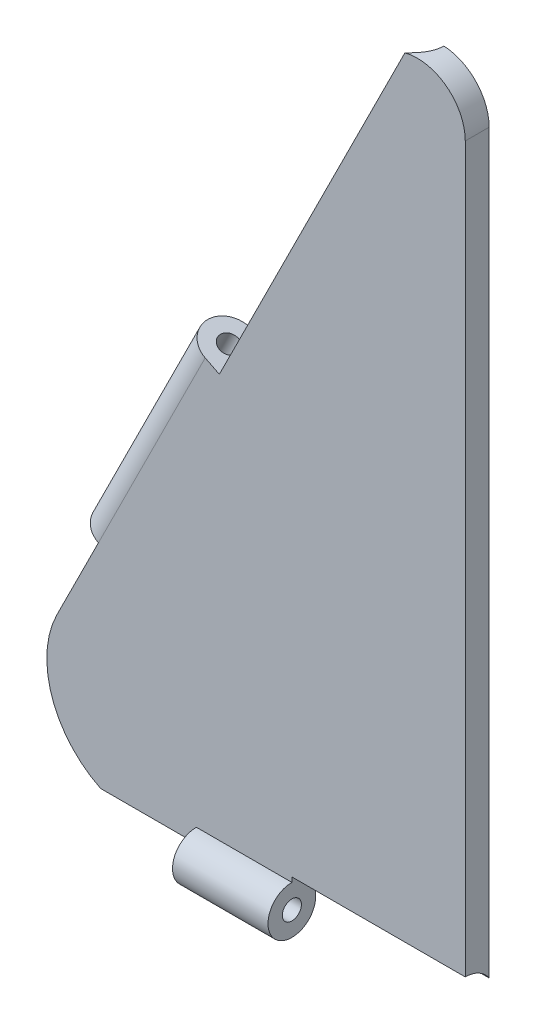
SolidWorks part; units mm, degrees
ref_plane "前视基准面" through (0, 0, 0) normal (0, 0, 1) x (1, 0, 0)
ref_plane "上视基准面" through (0, 0, 0) normal (0, 1, 0) x (1, 0, 0)
ref_plane "右视基准面" through (0, 0, 0) normal (1, 0, 0) x (0, 0, -1)
sketch "草图1" plane through (0, 0, 5) normal (0, 0, 1) x (1, 0, 0)
  line L0 (-531.2593, 335.4243) -> (-597.8429, 202.2571)
  line L1 (-579.9544, 173.3129) -> (-512.3151, 173.3129)
  line L2 (-512.3151, 173.3129) -> (-512.3151, 330.9522)
  arc A0 (-579.9544, 173.3129) -> (-597.8429, 202.2571) centre (-579.9544, 193.3129) cw
  arc A1 (-512.3151, 330.9522) -> (-531.2593, 335.4243) centre (-522.3151, 330.9522) ccw
  point P5 (-612.3151, 173.3129)
  point P8 (-512.3151, 373.3129)
  dimension "D3" = 20
  dimension "D4" = 10
  dimension "D1" = 200
  dimension "D2" = 100
extrude "凸台-拉伸1" add sketch "草图1" along normal blind 5
sketch "草图2" plane through (0, 173.3129, 0) normal (0, -1, 0) x (1, 0, 0)
  line L7 (-546.1347, 5) -> (-546.1347, 10) construction
  line L8 (-579.9544, 5) -> (-512.3151, 5) construction
  line L9 (-579.9544, 10) -> (-512.3151, 10) construction
  line L10 (-548.6347, 5) -> (-568.6347, 5)
  line L11 (-548.6347, 5) -> (-548.6347, 10)
  line L12 (-548.6347, 10) -> (-568.6347, 10)
  line L13 (-568.6347, 5) -> (-568.6347, 10)
  dimension "D1" = 20
  dimension "D2" = 2.5
sketch "草图3" plane through (-559.1772, 279.5886, 0) normal (-0.8944, 0.4472, 0) x (0, 0, 1)
  line L0 (10, -12.0165) -> (5, -12.0165) construction
  line L1 (10, 62.4262) -> (10, -86.4592) construction
  line L2 (5, 62.4262) -> (5, -86.4592) construction
  line L4 (10, -17.0165) -> (5, -17.0165)
  line L5 (10, -17.0165) -> (10, -67.0165)
  line L6 (10, -67.0165) -> (5, -67.0165)
  line L7 (5, -17.0165) -> (5, -67.0165)
  point P11 (7.5, -17.0165)
  dimension "D1" = 5
  dimension "D2" = 50
revolve "旋转1" add sketch "草图3" angle 360 about L7
sketch "草图5" plane through (-7.61, -15.22, 0) normal (0.4472, 0.8944, 0) x (0.8944, -0.4472, 0)
  circle A0 centre (-625.1791, -5) radius 2
  circle A1 centre (-625.1791, -5) radius 6
extrude "切除-拉伸1" cut sketch "草图5" against normal through all both and the other way through all contours A0
sketch "草图7" plane through (-7.61, -15.22, 0) normal (0.4472, 0.8944, 0) x (0.8944, -0.4472, 0)
  circle A0 centre (-625.1791, -5) radius 6
extrude "切除-拉伸2" cut sketch "草图7" along normal through all
revolve "旋转2" add sketch "草图2" angle 360 about L12
sketch "草图8" plane through (-548.6347, 0, 0) normal (1, 0, 0) x (0, 0, -1)
  circle A0 centre (-10, 173.3129) radius 6
extrude "切除-拉伸3" cut sketch "草图8" along normal through all
sketch "草图9" plane through (-568.6347, 0, 0) normal (-1, 0, 0) x (0, 0, 1)
  circle A0 centre (10, 173.3129) radius 2
extrude "切除-拉伸4" cut sketch "草图9" against normal through all both and the other way through all
scale "缩放比例1" scale about origin uniform scaling yes scale factor 0.5
